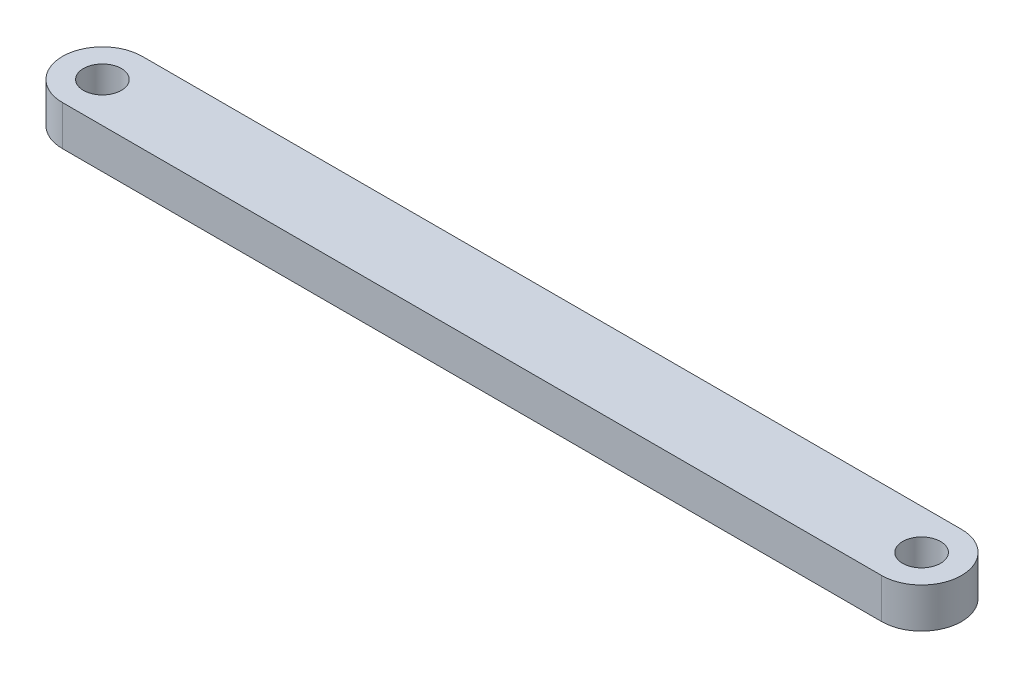
SolidWorks part; units mm, degrees
ref_plane "Front Plane" through (0, 0, 0) normal (0, 0, 1) x (1, 0, 0)
ref_plane "Top Plane" through (0, 0, 0) normal (0, 1, 0) x (1, 0, 0)
ref_plane "Right Plane" through (0, 0, 0) normal (1, 0, 0) x (0, 0, -1)
sketch "Sketch1" plane through (0, 0, 0) normal (0, 1, 0) x (1, 0, 0)
  line L0 (0, 2) -> (41, 2)
  line L1 (0, -2) -> (41, -2)
  circle A0 centre (0, 0) radius 0.95
  circle A1 centre (41, 0) radius 0.95
  arc A2 (0, 2) -> (0, -2) centre (0, 0) ccw
  arc A3 (41, -2) -> (41, 2) centre (41, 0) ccw
  dimension "D1" = 1.9
  dimension "D3" = 2
  dimension "D2" = 41
extrude "Boss-Extrude1" add sketch "Sketch1" along normal blind 2
